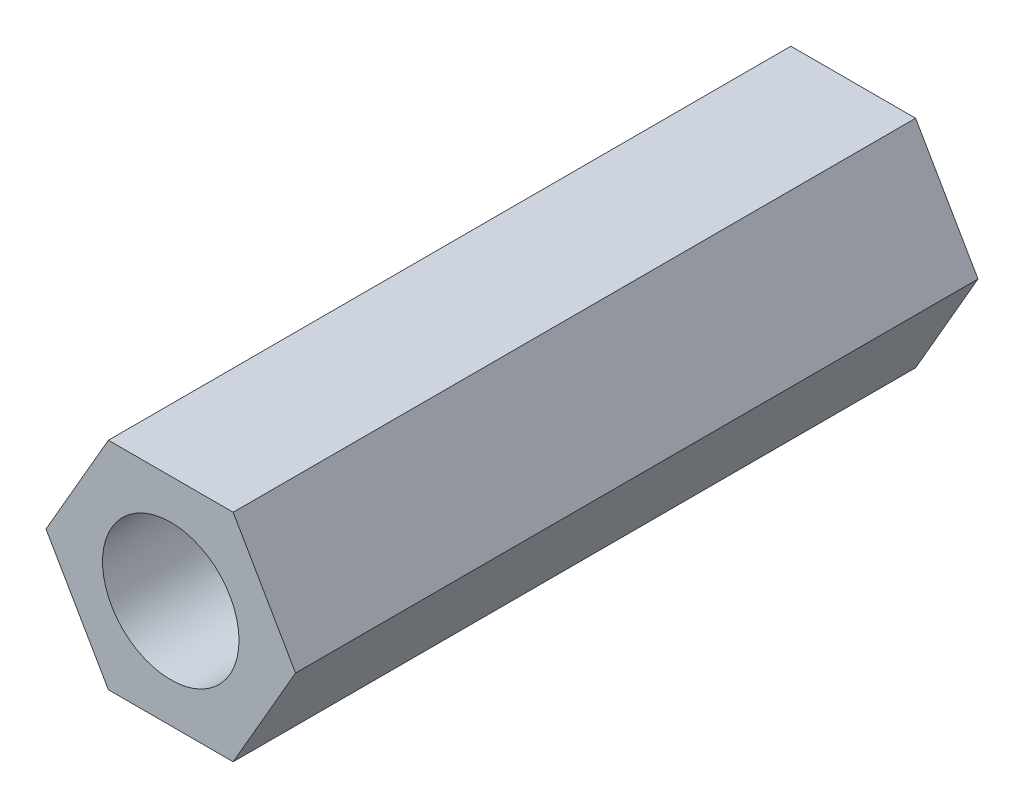
SolidWorks part; units mm, degrees
material "铸造不锈钢"
ref_plane "前视基准面" through (0, 0, 0) normal (0, 0, 1) x (1, 0, 0)
ref_plane "上视基准面" through (0, 0, 0) normal (0, 1, 0) x (1, 0, 0)
ref_plane "右视基准面" through (0, 0, 0) normal (1, 0, 0) x (0, 0, -1)
other "Configuration Table"
sketch "草图1" plane through (0, 0, 0) normal (0, 0, 1) x (1, 0, 0)
  line L1 (2.7424, 0) -> (1.3712, 2.375)
  line L2 (1.3712, 2.375) -> (-1.3712, 2.375)
  line L3 (-1.3712, 2.375) -> (-2.7424, 0)
  line L4 (-2.7424, 0) -> (-1.3712, -2.375)
  line L5 (-1.3712, -2.375) -> (1.3712, -2.375)
  line L6 (1.3712, -2.375) -> (2.7424, 0)
  circle A0 centre (0, 0) radius 2.375 construction
  circle A1 centre (0, 0) radius 1.5
  dimension "D2" = 3
  dimension "D1" = 4.75
extrude "凸台-拉伸1" add sketch "草图1" along normal blind 15
